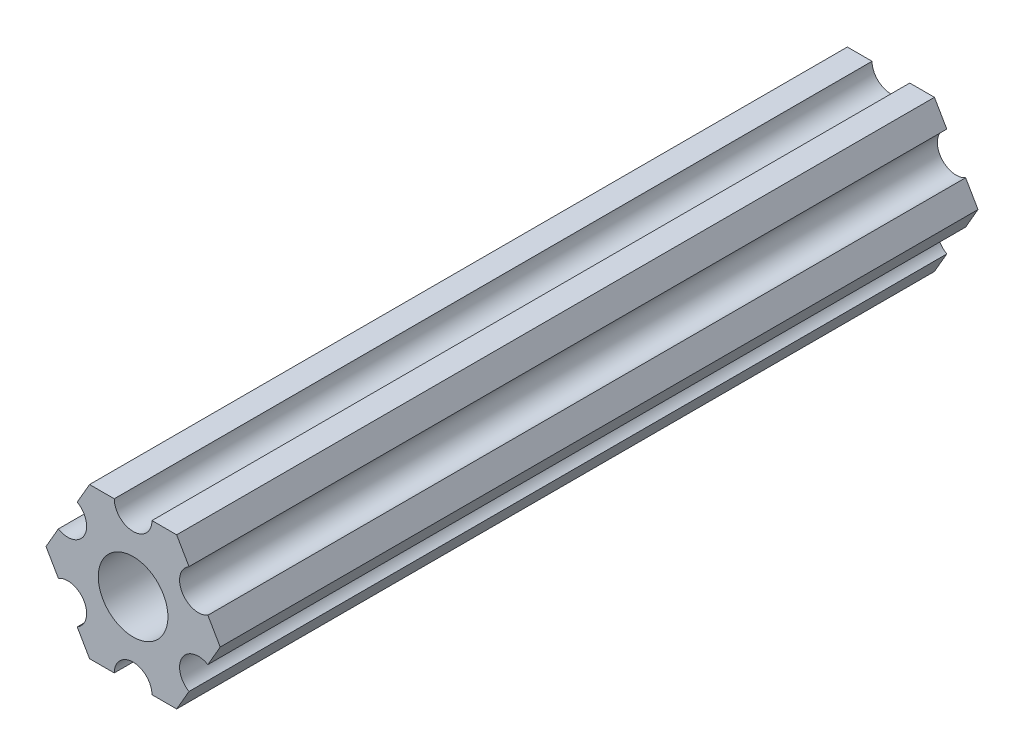
SolidWorks part; units mm, degrees
ref_plane "Front Plane" through (0, 0, 0) normal (0, 0, 1) x (1, 0, 0)
ref_plane "Top Plane" through (0, 0, 0) normal (0, 1, 0) x (1, 0, 0)
ref_plane "Right Plane" through (0, 0, 0) normal (1, 0, 0) x (0, 0, -1)
ref_plane "Plane1" through (0, 0, 0) normal (0, 0, -1) x (-1, 0, 0)
sketch "Sketch1" plane through (0, 0, 0) normal (0, 0, -1) x (-1, 0, 0)
  line L0 (-4.7055, -4.5498) -> (-3.6662, -6.35)
  line L1 (-3.6662, -6.35) -> (-1.5875, -6.35)
  line L2 (1.5875, -6.35) -> (3.6662, -6.35)
  line L3 (3.6662, -6.35) -> (4.7055, -4.5498)
  line L4 (6.293, -1.8002) -> (7.3323, 0)
  line L5 (7.3323, 0) -> (6.293, 1.8002)
  line L6 (4.7055, 4.5498) -> (3.6662, 6.35)
  line L7 (3.6662, 6.35) -> (1.5875, 6.35)
  line L8 (-1.5875, 6.35) -> (-3.6662, 6.35)
  line L9 (-3.6662, 6.35) -> (-4.7055, 4.5498)
  line L10 (-6.293, 1.8002) -> (-7.3323, 0)
  line L11 (-7.3323, 0) -> (-6.293, -1.8002)
  circle A0 centre (0, 0) radius 2.9337
  arc A1 (-6.293, -1.8002) -> (-4.7055, -4.5498) centre (-5.4993, -3.175) cw
  arc A2 (-1.5875, -6.35) -> (1.5875, -6.35) centre (0, -6.35) cw
  arc A3 (4.7055, -4.5498) -> (6.293, -1.8002) centre (5.4993, -3.175) cw
  arc A4 (6.293, 1.8002) -> (4.7055, 4.5498) centre (5.4993, 3.175) cw
  arc A5 (1.5875, 6.35) -> (-1.5875, 6.35) centre (0, 6.35) cw
  arc A6 (-4.7055, 4.5498) -> (-6.293, 1.8002) centre (-5.4993, 3.175) cw
extrude "Boss-Extrude1" add sketch "Sketch1" against normal blind 63.79
